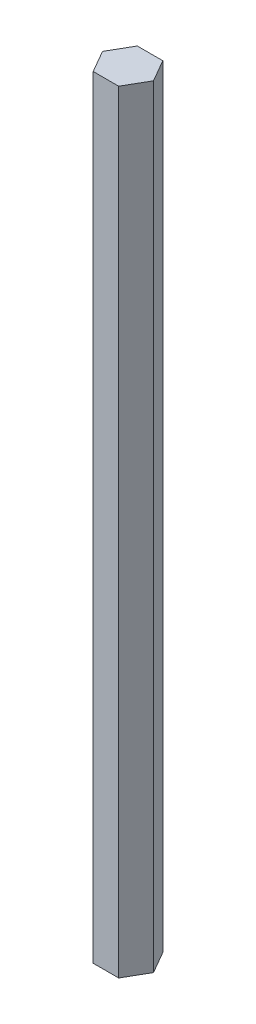
SolidWorks part; units mm, degrees
ref_plane "Front Plane" through (0, 0, 0) normal (0, 0, 1) x (1, 0, 0)
ref_plane "Top Plane" through (0, 0, 0) normal (0, 1, 0) x (1, 0, 0)
ref_plane "Right Plane" through (0, 0, 0) normal (1, 0, 0) x (0, 0, -1)
sketch "Sketch1" plane through (0, 0, 0) normal (0, 1, 0) x (1, 0, 0)
  line L1 (3.6662, -6.35) -> (7.3323, 0)
  line L2 (7.3323, 0) -> (3.6662, 6.35)
  line L3 (3.6662, 6.35) -> (-3.6662, 6.35)
  line L4 (-3.6662, 6.35) -> (-7.3323, 0)
  line L5 (-7.3323, 0) -> (-3.6662, -6.35)
  line L6 (-3.6662, -6.35) -> (3.6662, -6.35)
  circle A0 centre (0, 0) radius 6.35 construction
  dimension "D1" = 12.7
extrude "Boss-Extrude1" add sketch "Sketch1" along normal blind 222.25
